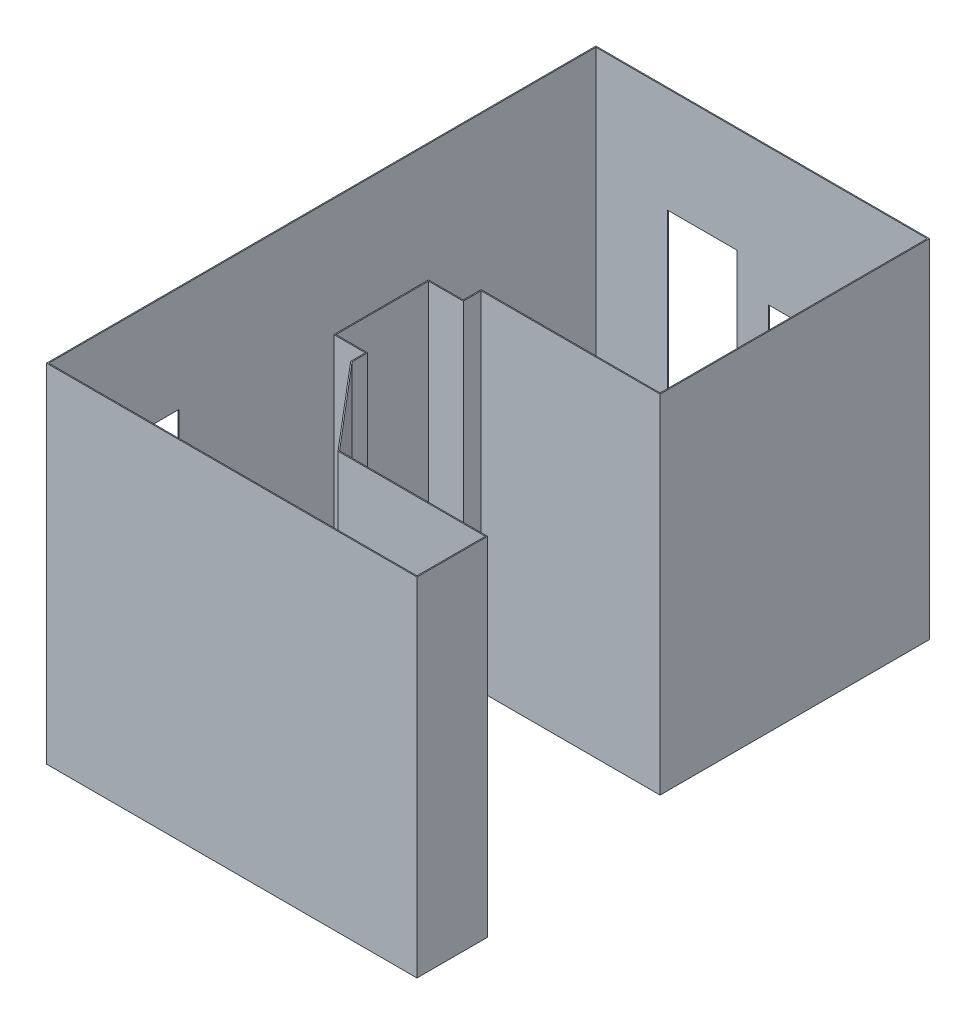
SolidWorks part; units mm, degrees
ref_plane "Спереди" through (0, 0, 0) normal (0, 0, 1) x (1, 0, 0)
ref_plane "Сверху" through (0, 0, 0) normal (0, 1, 0) x (1, 0, 0)
ref_plane "Справа" through (0, 0, 0) normal (1, 0, 0) x (0, 0, -1)
sketch "Эскиз1" plane through (0, 0, 0) normal (0, 1, 0) x (1, 0, 0)
  line L0 (0, 0) -> (0, 65)
  line L1 (0, 0) -> (-350, 0)
  line L2 (0, 65) -> (-140, 65)
  line L3 (-35.0074, 520) -> (-350, 520)
  line L4 (-350, 0) -> (-350, 520)
  line L5 (-140, 65) -> (-208.0074, 145)
  line L6 (-208.0074, 145) -> (-208.0074, 159)
  line L7 (-208.0074, 159) -> (-238.0074, 159)
  line L8 (-238.0074, 159) -> (-238.0074, 249)
  line L9 (-238.0074, 249) -> (-205.0074, 249)
  line L10 (-205.0074, 249) -> (-205.0074, 266)
  line L11 (-205.0074, 266) -> (-35.0074, 266)
  line L12 (-35.0074, 266) -> (-35.0074, 520)
  dimension "D2" = 350
  dimension "D3" = 65
  dimension "D4" = 140
  dimension "D5" = 105
  dimension "D6" = 14
  dimension "D7" = 30
  dimension "D8" = 90
  dimension "D9" = 170
  dimension "D10" = 33
  dimension "D11" = 17
  dimension "D12" = 520
  dimension "D13" = 254
  dimension "D14" = 90
extrude "Вытянуть-Тонкостенный2" add sketch "Эскиз1" along normal blind 330 thin
sketch "Эскиз2" plane through (0, 0, -521) normal (0, 0, -1) x (-1, 0, 0)
  line L0 (351, 330) -> (351, 0) construction
  line L1 (282, 10) -> (216, 10)
  line L2 (282, 10) -> (282, 230)
  line L3 (282, 230) -> (216, 230)
  line L4 (216, 10) -> (216, 230)
  line L5 (34.0074, 0) -> (351, 0) construction
  line L7 (186, 200) -> (41, 200)
  line L8 (186, 200) -> (186, 100)
  line L9 (186, 100) -> (41, 100)
  line L10 (41, 200) -> (41, 100)
  dimension "D1" = 69
  dimension "D2" = 66
  dimension "D3" = 10
  dimension "D4" = 220
  dimension "D5" = 145
  dimension "D6" = 100
  dimension "D7" = 30
  dimension "D8" = 100
extrude "Вырез-Вытянуть1" cut sketch "Эскиз2" against normal blind 10
sketch "Эскиз5" plane through (-351, 0, 0) normal (-1, 0, 0) x (0, 0, 1)
  line L0 (1, 330) -> (1, 0) construction
  line L1 (-124, 230) -> (-42, 230)
  line L2 (-124, 230) -> (-124, 10)
  line L3 (-124, 10) -> (-42, 10)
  line L4 (-42, 230) -> (-42, 10)
  line L5 (-521, 0) -> (1, 0) construction
  dimension "D1" = 220
  dimension "D2" = 82
  dimension "D3" = 43
  dimension "D4" = 10
extrude "Вырез-Вытянуть3" cut sketch "Эскиз5" against normal blind 10
sketch "Эскиз9" plane through (-49.1938, 0, 41.8193) normal (-0.7619, 0, 0.6477) x (0.6477, 0, 0.7619)
  line L0 (-140.2003, 0) -> (-245.2003, 0) construction
  line L1 (-235.2003, 230) -> (-170.2003, 230)
  line L2 (-235.2003, 230) -> (-235.2003, 10)
  line L3 (-235.2003, 10) -> (-170.2003, 10)
  line L4 (-170.2003, 230) -> (-170.2003, 10)
  line L5 (-140.2003, 330) -> (-140.2003, 0) construction
  dimension "D1" = 220
  dimension "D2" = 65
  dimension "D3" = 10
  dimension "D4" = 30
extrude "Вырез-Вытянуть5" cut sketch "Эскиз9" against normal blind 10
